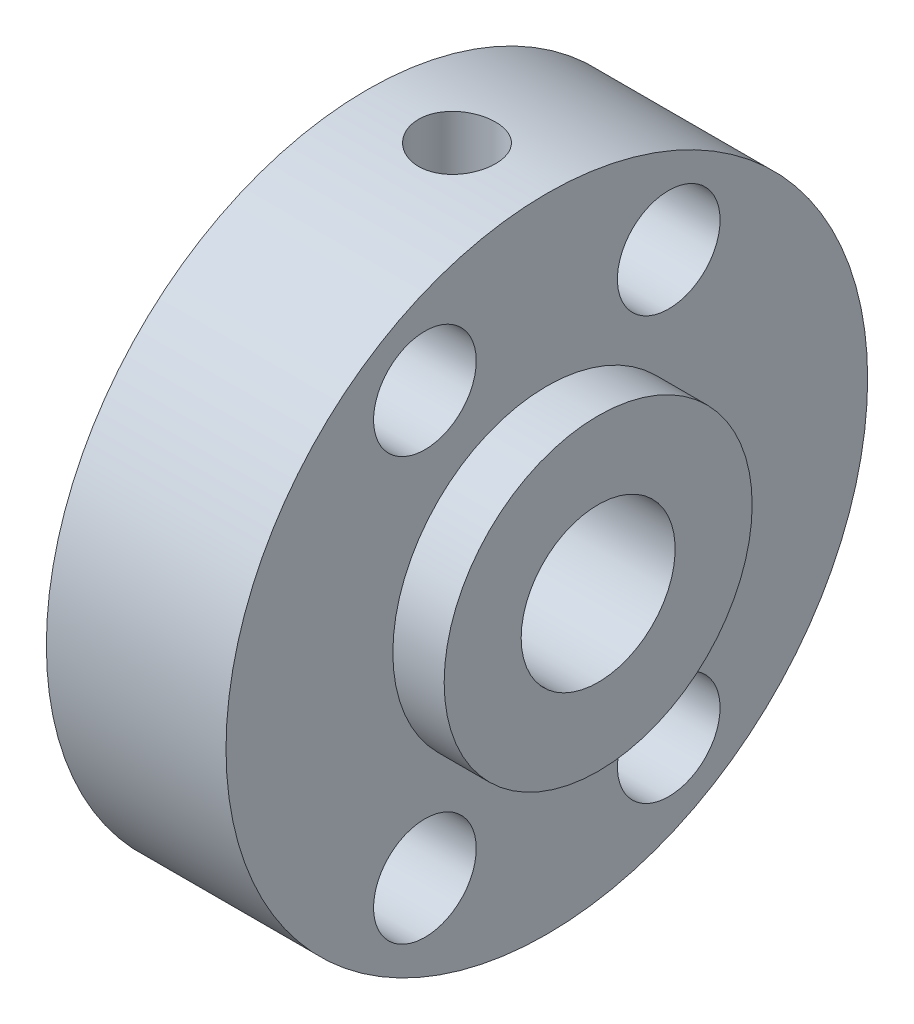
SolidWorks part; units mm, degrees
ref_plane "Plan de face" through (0, 0, 0) normal (0, 0, 1) x (1, 0, 0)
ref_plane "Plan de dessus" through (0, 0, 0) normal (0, 1, 0) x (1, 0, 0)
ref_plane "Plan de droite" through (0, 0, 0) normal (1, 0, 0) x (0, 0, -1)
sketch "Esquisse1" plane through (0, 0, 0) normal (0, 0, 1) x (1, 0, 0)
  line L0 (0, 0) -> (9, 0) construction
  line L1 (0, 3) -> (0, 12.5)
  line L2 (0, 12.5) -> (7, 12.5)
  line L3 (7, 12.5) -> (7, 6)
  line L4 (7, 6) -> (9, 6)
  line L5 (9, 6) -> (9, 3)
  line L6 (9, 3) -> (0, 3)
  dimension "D1" = 6
  dimension "D2" = 9
  dimension "D3" = 7
  dimension "D4" = 25
  dimension "D5" = 12
revolve "Révolution1" add sketch "Esquisse1" angle 360 about L0
sketch "Esquisse2" plane through (7, 0, 0) normal (1, 0, 0) x (0, 0, -1)
  line L0 (-4.75, 8.2272) -> (4.75, -8.2272) construction
  line L1 (4.75, 8.2272) -> (-4.75, -8.2272) construction
  circle A2 centre (-4.75, 8.2272) radius 2
  circle A3 centre (4.75, 8.2272) radius 2
  circle A4 centre (-4.75, -8.2272) radius 2
  circle A5 centre (4.75, -8.2272) radius 2
  point P4 (0, 0)
  dimension "D1" = 60
  dimension "D2" = 9.5
  dimension "D5" = 4
  dimension "D6" = 4
  dimension "D7" = 4
  dimension "D8" = 4
  dimension "D3" = 9.5
  dimension "D4" = 30
extrude "Enlèv. mat.-Extru.1" cut sketch "Esquisse2" against normal through all
sketch "Esquisse3" plane through (0, 0, 0) normal (0, 1, 0) x (1, 0, 0)
  circle A0 centre (3.5, 0) radius 1.5
  dimension "D1" = 3
  dimension "D2" = 3.5
extrude "Enlèv. mat.-Extru.2" cut sketch "Esquisse3" along normal blind 30
move or copy body "Body-Move/Copy1" [suppressed] bodies to move or copy 103
